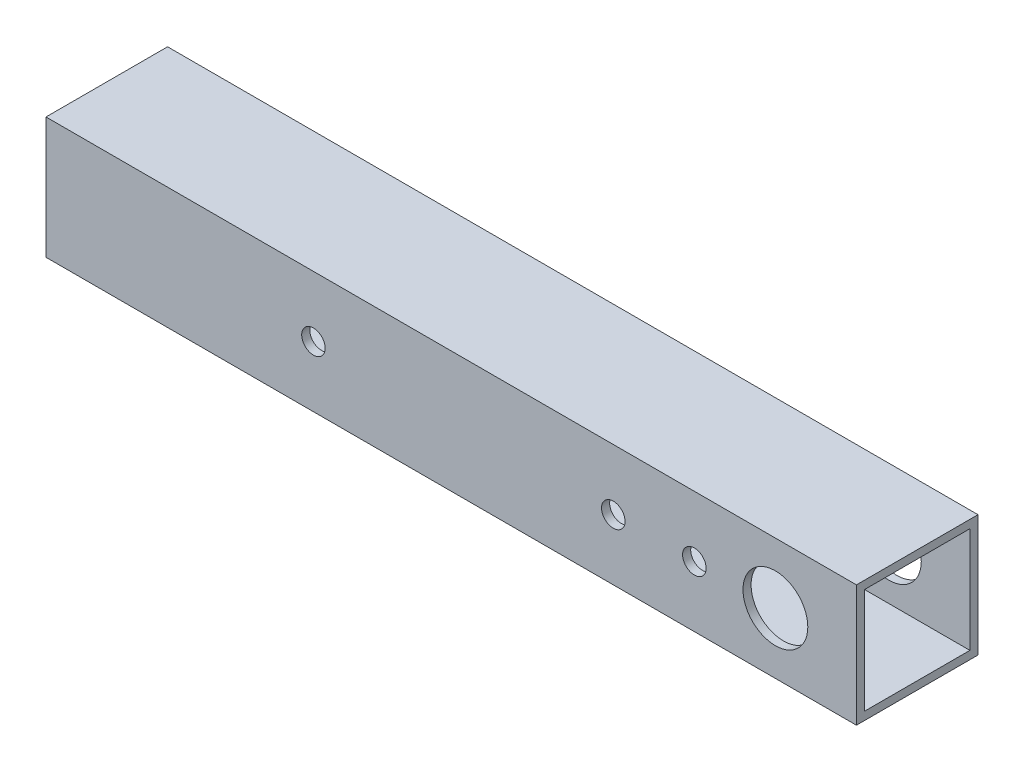
SolidWorks part; units mm, degrees
material "Thornel Mat VMA"
ref_plane "前视基准面" through (0, 0, 0) normal (0, 0, 1) x (1, 0, 0)
ref_plane "上视基准面" through (0, 0, 0) normal (0, 1, 0) x (1, 0, 0)
ref_plane "右视基准面" through (0, 0, 0) normal (1, 0, 0) x (0, 0, -1)
sketch "草图1" plane through (0, 0, 0) normal (0, 0, 1) x (1, 0, 0)
  line L0 (0, 0) -> (100, 0)
  dimension "D1" = 100
other "铝管 15X15X1(1)"
ref_plane "基准面4" through (0, 0, 0) normal (1, 0, 0) x (0, 1, 0)
sketch "草图11" plane through (0, 0, 0) normal (1, 0, 0) x (0, 1, 0)
  line L1 (-7.5, -7.5) -> (7.5, -7.5)
  line L2 (-7.5, -7.5) -> (-7.5, 7.5)
  line L3 (-7.5, 7.5) -> (7.5, 7.5)
  line L4 (7.5, -7.5) -> (7.5, 7.5)
  line L5 (-7.5, -7.5) -> (7.5, 7.5) construction
  line L6 (-7.5, 7.5) -> (7.5, -7.5) construction
  line L7 (-6.5, -6.5) -> (6.5, -6.5)
  line L8 (-6.5, -6.5) -> (-6.5, 6.5)
  line L9 (-6.5, 6.5) -> (6.5, 6.5)
  line L10 (6.5, -6.5) -> (6.5, 6.5)
  line L11 (-6.5, -6.5) -> (6.5, 6.5) construction
  line L12 (-6.5, 6.5) -> (6.5, -6.5) construction
  point P0 (0, 0)
  point P6 (0, 0)
  point P11 (0, 0)
  dimension "D1" = 15
  dimension "D2" = 15
  dimension "D3" = 13
  dimension "D4" = 13
sketch "草图12" plane through (0, 0, 7.5) normal (0, 0, 1) x (1, 0, 0)
  line L0 (0, 0) -> (100, 0) construction
  line L1 (0, 7.5) -> (0, -7.5) construction
  circle A0 centre (33, 0) radius 1.45
  dimension "D1" = 2.9
  dimension "D2" = 33
extrude "切除-拉伸1" cut sketch "草图12" against normal blind 22
sketch "草图13" plane through (0, 0, 7.5) normal (0, 0, 1) x (1, 0, 0)
  line L0 (100, 0) -> (0, 0) construction
  line L1 (100, 7.5) -> (100, -7.5) construction
  circle A0 centre (90, 0) radius 4
  circle A1 centre (80, 0) radius 1.45
  circle A2 centre (70, 0) radius 1.45
  dimension "D1" = 10
  dimension "D2" = 10
  dimension "D3" = 10
  dimension "D4" = 8
  dimension "D5" = 2.9
extrude "切除-拉伸2" cut sketch "草图13" against normal through all
